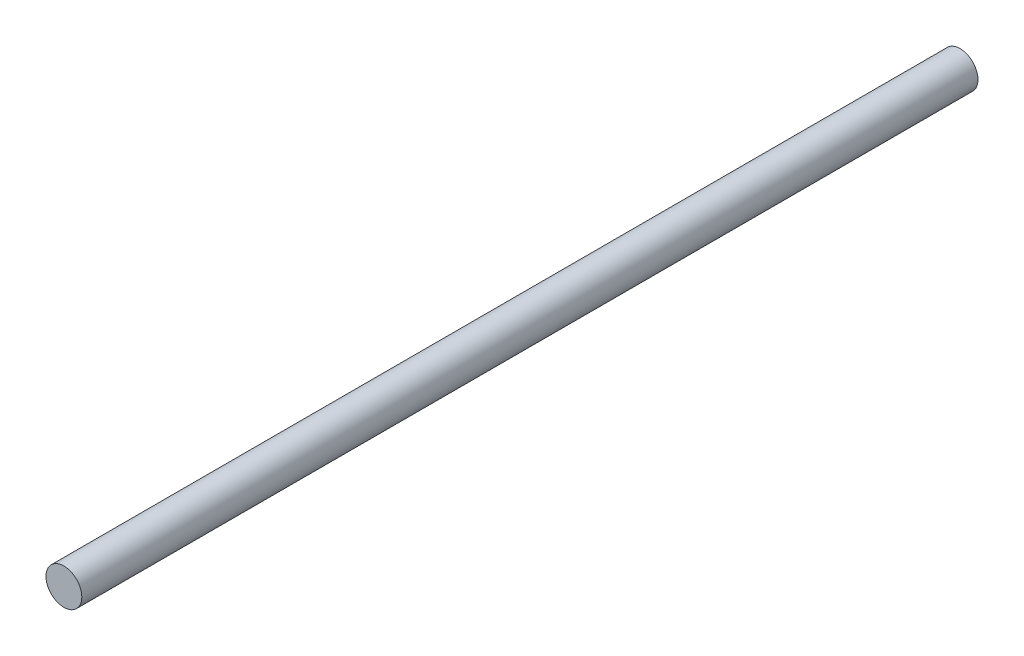
SolidWorks part; units mm, degrees
ref_plane "前视基准面" through (0, 0, 0) normal (0, 0, 1) x (1, 0, 0)
ref_plane "上视基准面" through (0, 0, 0) normal (0, 1, 0) x (1, 0, 0)
ref_plane "右视基准面" through (0, 0, 0) normal (1, 0, 0) x (0, 0, -1)
sketch "草图1" plane through (0, 0, 0) normal (0, 0, 1) x (1, 0, 0)
  circle A0 centre (0, 0) radius 10
  dimension "D1" = 20
extrude "凸台-拉伸1" add sketch "草图1" along normal blind 500 contours A0
